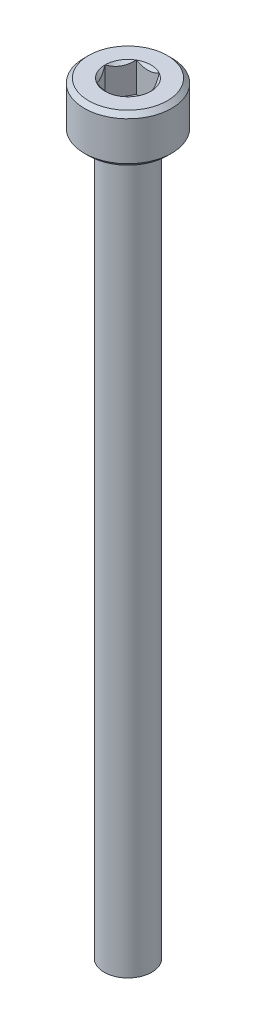
SolidWorks part; units mm, degrees
ref_plane "Front" through (0, 0, 0) normal (0, 0, 1) x (1, 0, 0)
ref_plane "Top" through (0, 0, 0) normal (0, 1, 0) x (1, 0, 0)
ref_plane "Right" through (0, 0, 0) normal (1, 0, 0) x (0, 0, -1)
sketch "Sketch1" plane through (0, 0, 0) normal (0, 1, 0) x (1, 0, 0)
  circle A0 centre (0, 0) radius 2.75
  dimension "D1" = 5.5
extrude "Boss-Extrude1" add sketch "Sketch1" along normal blind 3
sketch "Sketch2" plane through (0, 3, 0) normal (0, 1, 0) x (1, 0, 0)
  line L1 (0.7217, 1.25) -> (-0.7217, 1.25)
  line L2 (-0.7217, 1.25) -> (-1.4434, 0)
  line L3 (-1.4434, 0) -> (-0.7217, -1.25)
  line L4 (-0.7217, -1.25) -> (0.7217, -1.25)
  line L5 (0.7217, -1.25) -> (1.4434, 0)
  line L6 (1.4434, 0) -> (0.7217, 1.25)
  circle A0 centre (0, 0) radius 1.25 construction
  point P10 (0, 1.25)
  dimension "D1" = 2.5
extrude "Cut-Extrude1" cut sketch "Sketch2" against normal blind 1.88
sketch "Sketch5" plane through (0, 3, 0) normal (0, 1, 0) x (1, 0, 0)
  circle A0 centre (0, 0) radius 1.4434
extrude "Cut-Extrude2" cut sketch "Sketch5" against normal through all draft 45
chamfer "Chamfer1" distance 0.275 angle 45 2 edges at (0, 0, 2.75) (0, 3, 2.75)
sketch "草图1" plane through (0, 0, 0) normal (0, -1, 0) x (-1, 0, 0)
  circle A0 centre (0, 0) radius 1.5
  dimension "D1" = 3
extrude "凸台-拉伸1" add sketch "草图1" along normal blind 45
